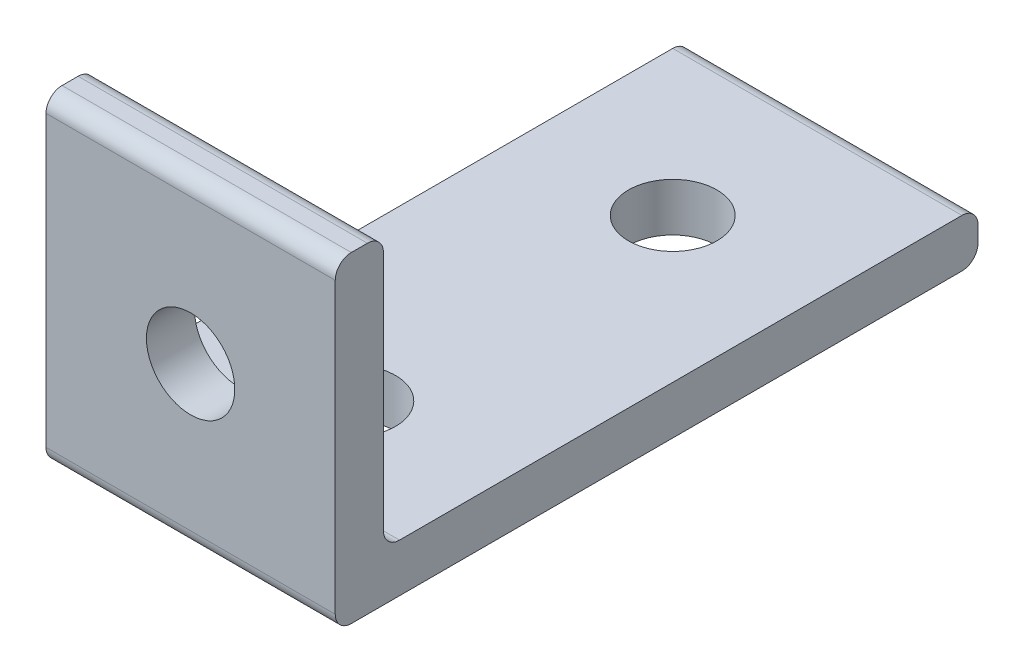
SolidWorks part; units mm, degrees
ref_plane "前视基准面" through (0, 0, 0) normal (0, 0, 1) x (1, 0, 0)
ref_plane "上视基准面" through (0, 0, 0) normal (0, 1, 0) x (1, 0, 0)
ref_plane "右视基准面" through (0, 0, 0) normal (1, 0, 0) x (0, 0, -1)
other "Configuration Table"
sketch "草图1" plane through (0, 0, 0) normal (1, 0, 0) x (0, 0, -1)
  line L1 (0, 0) -> (40, 0)
  line L2 (0, 0) -> (0, 20)
  line L3 (0, 20) -> (40, 20)
  line L4 (40, 0) -> (40, 20)
  dimension "D1" = 40
  dimension "D2" = 20
extrude "凸台-拉伸1" add sketch "草图1" along normal blind 18
sketch "草图2" plane through (18, 0, 0) normal (1, 0, 0) x (0, 0, -1)
  line L0 (3, 20) -> (3, 3)
  line L1 (40, 20) -> (0, 20) construction
  line L2 (3, 3) -> (40, 3)
  line L3 (40, 0) -> (40, 20) construction
  line L4 (40, 3) -> (40, 20)
  line L5 (40, 20) -> (3, 20)
  line L6 (0, 20) -> (0, 0) construction
  dimension "D1" = 17
  dimension "D2" = 3
extrude "切除-拉伸1" cut sketch "草图2" against normal blind 18
sketch "草图3" plane through (0, 0, -3) normal (0, 0, -1) x (-1, 0, 0)
  line L0 (-18, 20) -> (-18, 3) construction
  line L1 (0, 20) -> (-18, 20) construction
  circle A0 centre (-9, 10) radius 2.75
  dimension "D1" = 9
  dimension "D2" = 10
  dimension "D3" = 5.5
extrude "切除-拉伸2" cut sketch "草图3" against normal blind 18 contours A0
sketch "草图4" plane through (0, 3, 0) normal (0, 1, 0) x (1, 0, 0)
  line L0 (18, 3) -> (18, 40) construction
  line L1 (0, 40) -> (18, 40) construction
  circle A0 centre (9, 30) radius 2.75
  circle A1 centre (9, 10) radius 2.75
  dimension "D1" = 9
  dimension "D3" = 5.5
  dimension "D4" = 5.5
  dimension "D5" = 20
  dimension "D2" = 10
extrude "切除-拉伸3" cut sketch "草图4" against normal blind 18
fillet "圆角1" radius 1 6 edges at (9, 0, -40) (9, 3, -40) (9, 0, 0) (9, 20, 0) (9, 20, -3) (9, 3, -3)
